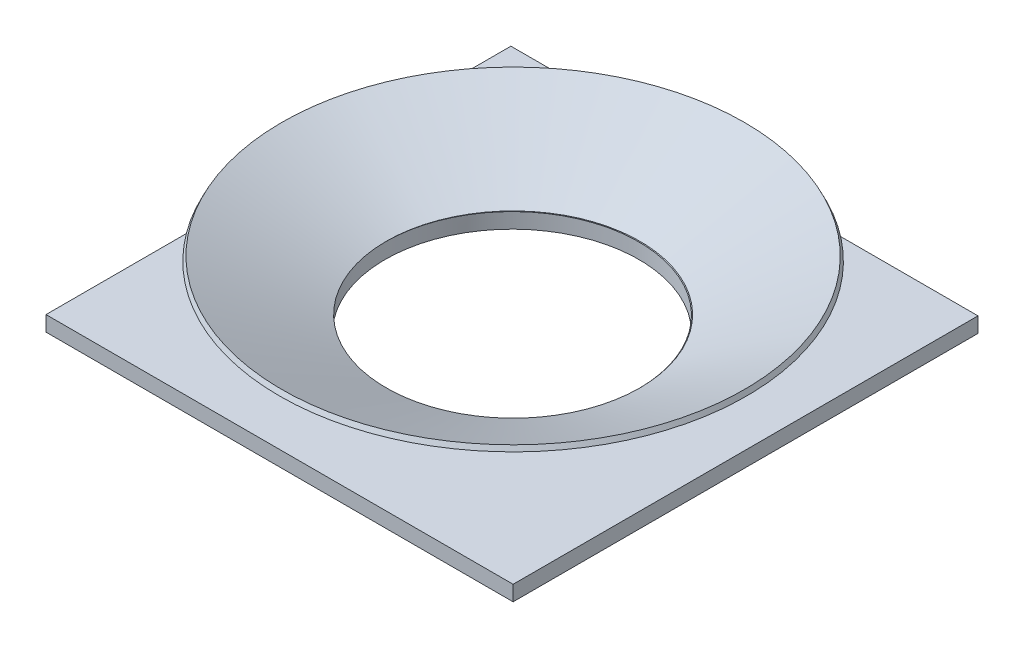
SolidWorks part; units mm, degrees
ref_plane "Front Plane" through (0, 0, 0) normal (0, 0, 1) x (1, 0, 0)
ref_plane "Top Plane" through (0, 0, 0) normal (0, 1, 0) x (1, 0, 0)
ref_plane "Right Plane" through (0, 0, 0) normal (1, 0, 0) x (0, 0, -1)
sketch "Sketch1" plane through (0, 0, 0) normal (0, 0, 1) x (1, 0, 0)
  line L0 (-27.2865, 0) -> (-46, 9.1007)
  line L1 (-46, 9.1007) -> (-45.5627, 10)
  line L2 (-45.5627, 10) -> (-25, 0)
  line L3 (-27.2865, 0) -> (-25, 0)
  line L4 (0, 0) -> (0, 38.049) construction
  line L5 (0, 0) -> (-37.9362, 0) construction
  dimension "D1" = 25
  dimension "D2" = 46
  dimension "D3" = 1
  dimension "D4" = 10
revolve "Revolve1" add sketch "Sketch1" angle 360 about L4
sketch "Sketch2" plane through (0, 0, 0) normal (0, 1, 0) x (1, 0, 0)
  line L0 (-46, -46) -> (46, -46)
  line L1 (-46, -46) -> (-46, 45.5627)
  line L2 (46, -46) -> (46, 45.5627)
  line L3 (-46, 45.5627) -> (46, 45.5627)
  line L4 (-46, -46) -> (46, 45.5627) construction
  line L5 (46, -46) -> (-46, 45.5627) construction
  circle A0 centre (0, -0.2187) radius 25
  circle A1 centre (0, 0) radius 46 construction
  circle A2 centre (0, 0) radius 45.5627 construction
  point P1 (0, -0.2187)
  dimension "D1" = 50
extrude "Boss-Extrude1" add sketch "Sketch2" against normal blind 3 separate body
sketch "Sketch3" plane through (0, 0, 0) normal (0, 0, 1) x (1, 0, 0)
  line L0 (-46, 9.1007) -> (-27.2865, 0) construction
  line L2 (-46, 0) -> (46, 0) construction
  line L4 (-27.2865, 0) -> (-30.4856, 1.5558)
  line L5 (-30.8439, 0) -> (-27.2865, 0)
  line L6 (0, 0) -> (0, 3.3138) construction
  arc A0 (-30.4856, 1.5558) -> (-30.8439, 0) centre (-30.8439, 0.8191) cw
revolve "Revolve2" add sketch "Sketch3" angle 360 about L6
